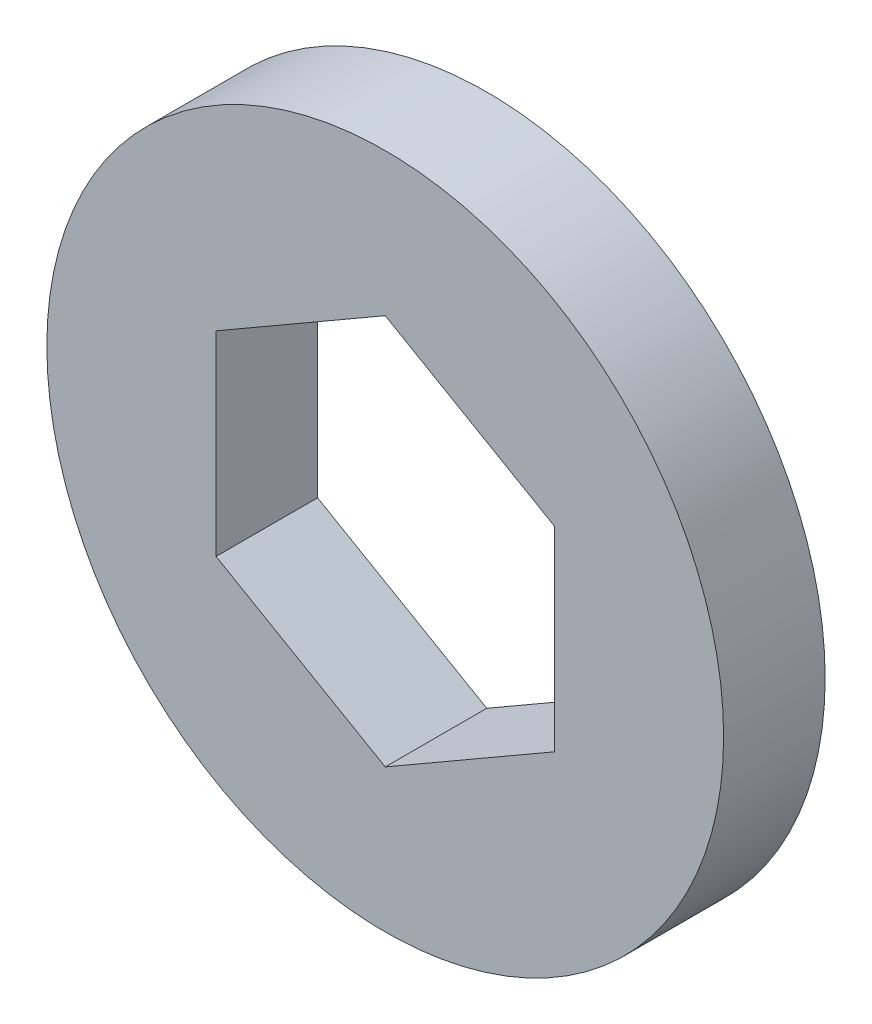
SolidWorks part; units mm, degrees
ref_plane "Front Plane" through (0, 0, 0) normal (0, 0, 1) x (1, 0, 0)
ref_plane "Top Plane" through (0, 0, 0) normal (0, 1, 0) x (1, 0, 0)
ref_plane "Right Plane" through (0, 0, 0) normal (1, 0, 0) x (0, 0, -1)
sketch "Sketch1" plane through (0, 0, 0) normal (0, 0, 1) x (1, 0, 0)
  line L1 (0, 28.8675) -> (-25, 14.4338)
  line L2 (-25, 14.4338) -> (-25, -14.4338)
  line L3 (-25, -14.4338) -> (0, -28.8675)
  line L4 (0, -28.8675) -> (25, -14.4338)
  line L5 (25, -14.4338) -> (25, 14.4338)
  line L6 (25, 14.4338) -> (0, 28.8675)
  circle A0 centre (0, 0) radius 25 construction
  circle A1 centre (0, 0) radius 50
  dimension "D1" = 50
  dimension "D2" = 100
extrude "Boss-Extrude1" add sketch "Sketch1" along normal blind 15
